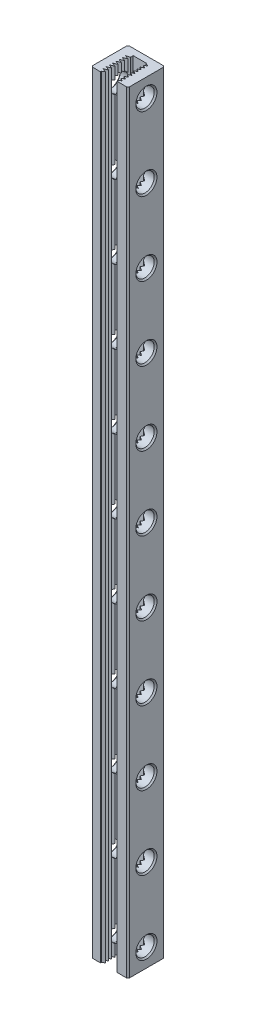
SolidWorks part; units mm, degrees
ref_plane "Front Plane" through (0, 0, 0) normal (0, 0, 1) x (1, 0, 0)
ref_plane "Top Plane" through (0, 0, 0) normal (0, 1, 0) x (1, 0, 0)
ref_plane "Right Plane" through (0, 0, 0) normal (1, 0, 0) x (0, 0, -1)
sketch "Sketch1" plane through (0, 0, 0) normal (0, 1, 0) x (1, 0, 0)
  line L1 (0, 0) -> (8, 0)
  line L2 (0, 0) -> (0, 8)
  line L3 (0, 8) -> (8, 8)
  line L4 (8, 0) -> (8, 8)
  dimension "D1" = 8
  dimension "D2" = 8
extrude "Boss-Extrude1" add sketch "Sketch1" along normal blind 300
sketch "Sketch2" plane through (0, 0, 0) normal (0, -1, 0) x (1, 0, 0)
  line L0 (5.652, 0) -> (2.0084, 0)
  line L1 (2.0084, 0) -> (2.0084, -0.2082)
  line L2 (2.0084, -0.2082) -> (2.54, -0.5151)
  line L3 (2.54, -0.5151) -> (1.6737, -0.8651)
  line L4 (1.6737, -0.8651) -> (2.54, -1.2151)
  line L5 (2.54, -1.2151) -> (1.6737, -1.5727)
  line L6 (1.6737, -1.5727) -> (2.54, -1.9151)
  line L7 (2.54, -1.9151) -> (1.6737, -2.2651)
  line L8 (1.6737, -2.2651) -> (2.54, -2.6151)
  line L9 (2.54, -2.6151) -> (1.6737, -2.9651)
  line L10 (1.6737, -2.9651) -> (2.54, -3.3151)
  line L11 (2.54, -3.3151) -> (1.6737, -3.6651)
  line L12 (1.6737, -3.6651) -> (2.54, -4.0151)
  line L13 (2.54, -4.0151) -> (1.6737, -4.3651)
  line L14 (1.6737, -4.3651) -> (2.54, -4.7151)
  line L15 (2.54, -4.7151) -> (1.6737, -5.0651)
  line L16 (1.6737, -5.0651) -> (2.54, -5.4151)
  line L17 (2.54, -5.4151) -> (1.6737, -5.7651)
  line L18 (1.6737, -5.7651) -> (2.54, -6.0264)
  line L19 (2.54, -6.0264) -> (2.54, -6.6)
  line L20 (2.54, -6.6) -> (5.46, -6.6)
  line L21 (5.46, -6.6) -> (5.46, -6.4988)
  line L22 (5.46, -6.4988) -> (6.1067, -6.2375)
  line L23 (6.1067, -6.2375) -> (5.46, -5.8875)
  line L24 (5.46, -5.8875) -> (6.1067, -5.5375)
  line L25 (6.1067, -5.5375) -> (5.46, -5.1875)
  line L26 (5.46, -5.1875) -> (6.1067, -4.8375)
  line L27 (6.1067, -4.8375) -> (5.46, -4.4875)
  line L28 (5.46, -4.4875) -> (6.1067, -4.1375)
  line L29 (6.1067, -4.1375) -> (5.46, -3.7875)
  line L30 (5.46, -3.7875) -> (6.1067, -3.4375)
  line L31 (6.1067, -3.4375) -> (5.46, -3.0875)
  line L32 (5.46, -3.0875) -> (6.1067, -2.7375)
  line L33 (6.1067, -2.7375) -> (5.46, -2.3875)
  line L34 (5.46, -2.3875) -> (6.1067, -2.0375)
  line L35 (6.1067, -2.0375) -> (5.46, -1.6875)
  line L36 (5.46, -1.6875) -> (6.1067, -1.3451)
  line L37 (6.1067, -1.3451) -> (5.46, -0.9875)
  line L38 (5.46, -0.9875) -> (6.1067, -0.6375)
  line L39 (6.1067, -0.6375) -> (5.652, -0.375)
  line L40 (5.652, -0.375) -> (5.652, 0)
  line L41 (0, -8) -> (0, 0) construction
  line L42 (8, -8) -> (0, -8) construction
  line L43 (0, 0) -> (8, 0) construction
  point P41 (0, 0)
  point P42 (0, 0)
  point P43 (0, 0)
  point P44 (0, 0)
  point P51 (0, 0)
  point P52 (0, 0)
  point P53 (4, -6.6)
  dimension "D1" = 2.92
  dimension "D2" = 0.8663
  dimension "D3" = 6.6
  dimension "D4" = 0.6467
  dimension "D5" = 4.433
  dimension "D6" = 4
extrude "Cut-Extrude1" cut sketch "Sketch2" against normal through all contours L0 L1 L2 L3 L4 L5 L6 L7 L8 L9 L10 L11 L12 L13 L14 L15 L16 L17 L18 L19 L20 L21 L22 L23 L24 L25 L26 L27 L28 L29 L30 L31 L32 L33 L34 L35 L36 L37 L38 L39 L40
sketch "Sketch3" plane through (8, 0, 0) normal (1, 0, 0) x (0, 0, -1)
  line L0 (0, 0) -> (8, 0) construction
  line L1 (8, 300) -> (8, 0) construction
  circle A0 centre (4, 4) radius 2
  dimension "D1" = 4
  dimension "D2" = 4
  dimension "D3" = 4
extrude "Cut-Extrude2" cut sketch "Sketch3" against normal through all
chamfer "Chamfer1" distance 0.3 angle 45 2 edges at (0, 4, -6) (8, 4, -6)
chamfer "Chamfer2" distance 0.3 angle 45 4 edges at (0, 150, -8) (0, 150, 0) (8, 150, -8) (8, 150, 0)
pattern_linear "LPattern1" count 19 spacing 16 along (0, 1, 0) of "Cut-Extrude2", "Chamfer1"
sketch "Sketch4" plane through (8, 0, 0) normal (1, 0, 0) x (0, 0, -1)
  line L0 (0.3, 300) -> (7.7, 300) construction
  line L1 (8, 300) -> (0, 300)
  line L2 (8, 300) -> (8, 168)
  line L3 (8, 168) -> (0, 168)
  line L4 (0, 300) -> (0, 168)
  line L5 (0, 0) -> (0, 300) construction
  line L6 (8, 300) -> (8, 0) construction
  line L7 (0.3, 0) -> (7.7, 0) construction
  point P7 (0, 0)
  dimension "D1" = 168
extrude "Cut-Extrude3" cut sketch "Sketch4" against normal through all
